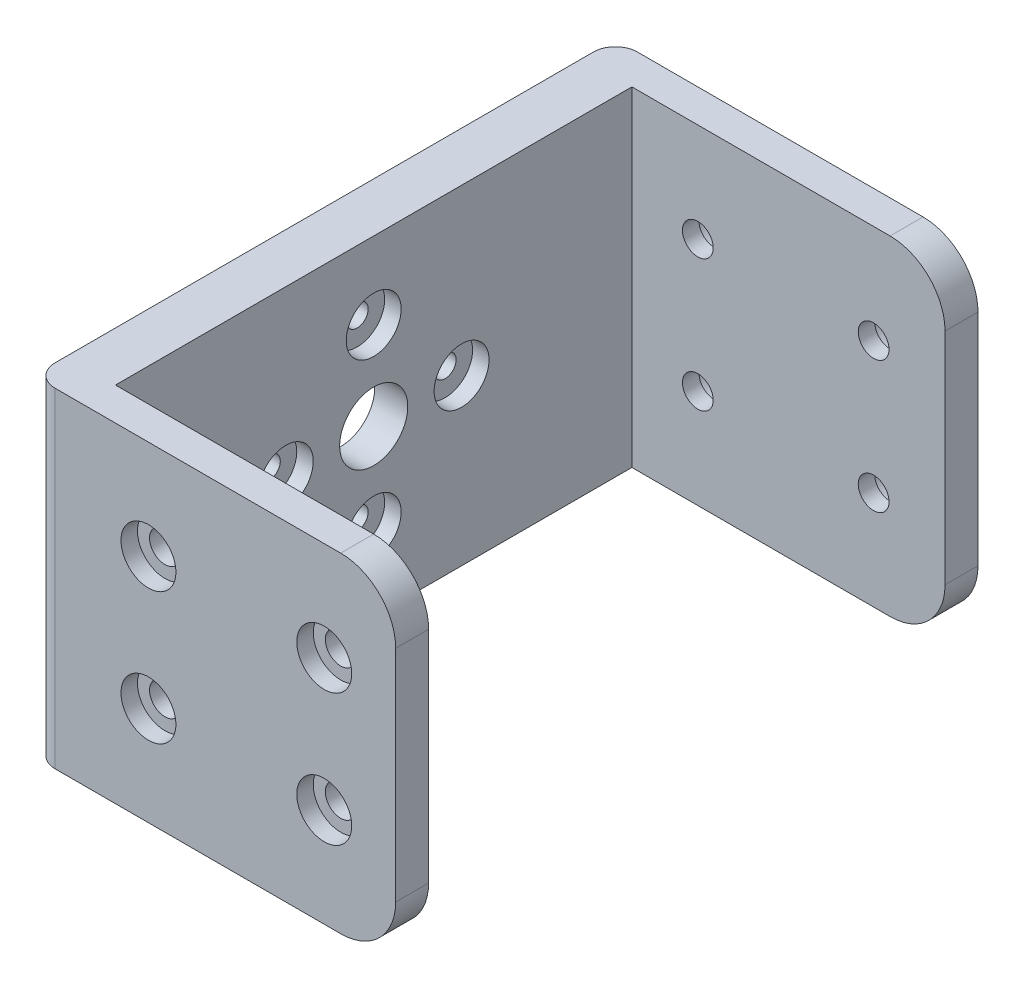
SolidWorks part; units mm, degrees
ref_plane "Front Plane" through (0, 0, 0) normal (0, 0, 1) x (1, 0, 0)
ref_plane "Top Plane" through (0, 0, 0) normal (0, 1, 0) x (1, 0, 0)
ref_plane "Right Plane" through (0, 0, 0) normal (1, 0, 0) x (0, 0, -1)
sketch "Sketch1" plane through (0, 0, 0) normal (0, 1, 0) x (1, 0, 0)
  line L0 (65.8235, -35.5588) -> (65.8235, -32.5588)
  line L1 (65.8235, -32.5588) -> (37.3235, -32.5588)
  line L2 (37.3235, -32.5588) -> (37.3235, 14.4412)
  line L3 (37.3235, 14.4412) -> (65.8235, 14.4412)
  line L4 (65.8235, 14.4412) -> (65.8235, 17.4412)
  line L5 (65.8235, 17.4412) -> (32.8235, 17.4412)
  line L6 (32.8235, 17.4412) -> (32.8235, -35.5588)
  line L7 (32.8235, -35.5588) -> (65.8235, -35.5588)
  dimension "D1" = 3
  dimension "D2" = 4.5
  dimension "D3" = 3
  dimension "D4" = 28.5
  dimension "D5" = 47
extrude "Boss-Extrude1" add sketch "Sketch1" along normal blind 30
sketch "Sketch2" plane through (0, 0, -17.4412) normal (0, 0, -1) x (-1, 0, 0)
  line L0 (-59.3235, 9) -> (-59.3235, 21) construction
  line L1 (-65.8235, 30) -> (-65.8235, 0) construction
  line L2 (-35.8235, 0) -> (-35.8235, 30) construction
  line L3 (-65.8235, 0) -> (-32.8235, 0) construction
  line L4 (-65.8235, 30) -> (-32.8235, 30) construction
  line L5 (-32.8235, 30) -> (-32.8235, 0) construction
  line L6 (-59.3235, 9) -> (-43.3235, 9) construction
  line L7 (-49.3235, 0) -> (-49.3235, 30) construction
  circle A0 centre (-59.3235, 9) radius 1.4
  circle A1 centre (-43.3235, 9) radius 1.4
  circle A2 centre (-43.3235, 21) radius 1.4
  circle A3 centre (-59.3235, 21) radius 1.4
  point P2 (-59.3235, 15)
  point P11 (-65.8235, 15)
  dimension "D1" = 2.8
  dimension "D4" = 3
  dimension "D5" = 10
  dimension "D2" = 2
  dimension "D3" = 2
extrude "Cut-Extrude1" cut sketch "Sketch2" against normal through all
sketch "Sketch3" plane through (0, 0, -17.4412) normal (0, 0, -1) x (-1, 0, 0)
  circle A0 centre (-59.3235, 9) radius 2.5
  circle A1 centre (-43.3235, 9) radius 2.5
  circle A2 centre (-43.3235, 21) radius 2.5
  circle A3 centre (-59.3235, 21) radius 2.5
  dimension "D1" = 5
  dimension "D2" = 2
  dimension "D3" = 2
extrude "Cut-Extrude2" cut sketch "Sketch3" against normal blind 1.5
sketch "Sketch4" plane through (0, 0, 35.5588) normal (0, 0, 1) x (1, 0, 0)
  circle A0 centre (59.3235, 21) radius 2.5
  circle A1 centre (43.3235, 21) radius 2.5
  circle A2 centre (43.3235, 9) radius 2.5
  circle A3 centre (59.3235, 9) radius 2.5
  dimension "D1" = 5
  dimension "D2" = 2
  dimension "D3" = 2
extrude "Cut-Extrude3" cut sketch "Sketch4" against normal blind 1.5
sketch "Sketch5" plane through (32.8235, 0, 0) normal (-1, 0, 0) x (0, 0, 1)
  line L0 (-17.4412, 30) -> (35.5588, 30) construction
  line L1 (-17.4412, 30) -> (-17.4412, 0) construction
  circle A0 centre (9.0588, 15) radius 11.4
  point P5 (9.0588, 30)
  point P9 (-17.4412, 15)
  dimension "D1" = 22.8
extrude "Cut-Extrude4" cut sketch "Sketch5" against normal blind 1.5
sketch "Sketch6" plane through (34.3235, 0, 0) normal (-1, 0, 0) x (0, 0, 1)
  circle A0 centre (9.0588, 15) radius 3.1
  circle A1 centre (9.0588, 15) radius 8 construction
  circle A2 centre (1.0588, 15) radius 1
  circle A3 centre (9.0588, 23) radius 1
  circle A4 centre (17.0588, 15) radius 1
  circle A5 centre (9.0588, 7) radius 1
  point P15 (9.0588, 15)
  dimension "D1" = 6.2
  dimension "D2" = 16
  dimension "D3" = 2
  dimension "D4" = 4
extrude "Cut-Extrude5" cut sketch "Sketch6" against normal through all
fillet "Fillet1" radius 5 4 edges at (65.8235, 0, 34.0588) (65.8235, 30, 34.0588) (65.8235, 0, -15.9412) (65.8235, 30, -15.9412)
fillet "Fillet2" radius 2 2 edges at (32.8235, 15, 35.5588) (32.8235, 15, -17.4412)
sketch "Sketch7" plane through (37.3235, 0, 0) normal (1, 0, 0) x (0, 0, -1)
  circle A0 centre (-17.0588, 15) radius 2.5
  circle A1 centre (-9.0588, 23) radius 2.5
  circle A2 centre (-1.0588, 15) radius 2.5
  circle A3 centre (-9.0588, 7) radius 2.5
  point P12 (-9.0588, 15)
  dimension "D1" = 5
  dimension "D2" = 4
extrude "Cut-Extrude6" cut sketch "Sketch7" against normal blind 1.5
